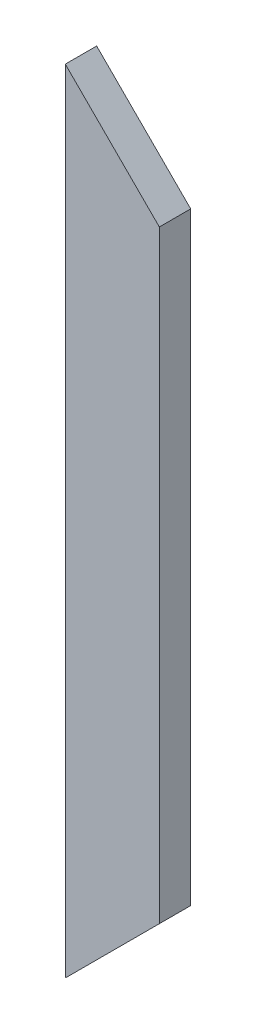
SolidWorks part; units mm, degrees
material "AISI 1020"
ref_plane "Front Plane" through (0, 0, 0) normal (0, 0, 1) x (1, 0, 0)
ref_plane "Top Plane" through (0, 0, 0) normal (0, 1, 0) x (1, 0, 0)
ref_plane "Right Plane" through (0, 0, 0) normal (1, 0, 0) x (0, 0, -1)
sketch "Sketch1" plane through (0, 0, 0) normal (0, 0, 1) x (1, 0, 0)
  line L1 (-38.1, -320.675) -> (38.1, -320.675)
  line L2 (-38.1, -320.675) -> (-38.1, 320.675)
  line L3 (-38.1, 320.675) -> (38.1, 320.675)
  line L4 (38.1, -320.675) -> (38.1, 320.675)
  line L5 (-38.1, -320.675) -> (38.1, 320.675) construction
  line L6 (-38.1, 320.675) -> (38.1, -320.675) construction
  point P0 (0, 0)
  dimension "D1" = 641.35
  dimension "D2" = 76.2
extrude "Boss-Extrude1" add sketch "Sketch1" along normal blind 25.4
sketch "Sketch2" plane through (0, 0, 25.4) normal (0, 0, 1) x (1, 0, 0)
  line L0 (-38.1, -320.675) -> (38.1, -244.475)
  line L1 (38.1, -320.675) -> (38.1, 320.675) construction
  line L2 (-38.1, -320.675) -> (38.1, -320.675) construction
  line L3 (38.1, -244.475) -> (38.1, -320.675)
  line L4 (38.1, -320.675) -> (-38.1, -320.675)
  dimension "D1" = 45
extrude "Cut-Extrude1" cut sketch "Sketch2" against normal blind 25.4
sketch "Sketch3" plane through (0, 0, 25.4) normal (0, 0, 1) x (1, 0, 0)
  line L0 (-38.1, 320.675) -> (38.1, 244.475)
  line L1 (38.1, -244.475) -> (38.1, 320.675) construction
  line L2 (38.1, 244.475) -> (38.1, 320.675)
  line L3 (38.1, 320.675) -> (-38.1, 320.675)
  dimension "D1" = 45
extrude "Cut-Extrude2" cut sketch "Sketch3" against normal blind 25.4
equation "\"A\"= 100"
equation "\"B\"= 100"
equation "\"C\"= 100"
equation "\"D\"= 100"
equation "\"E\"= 100"
